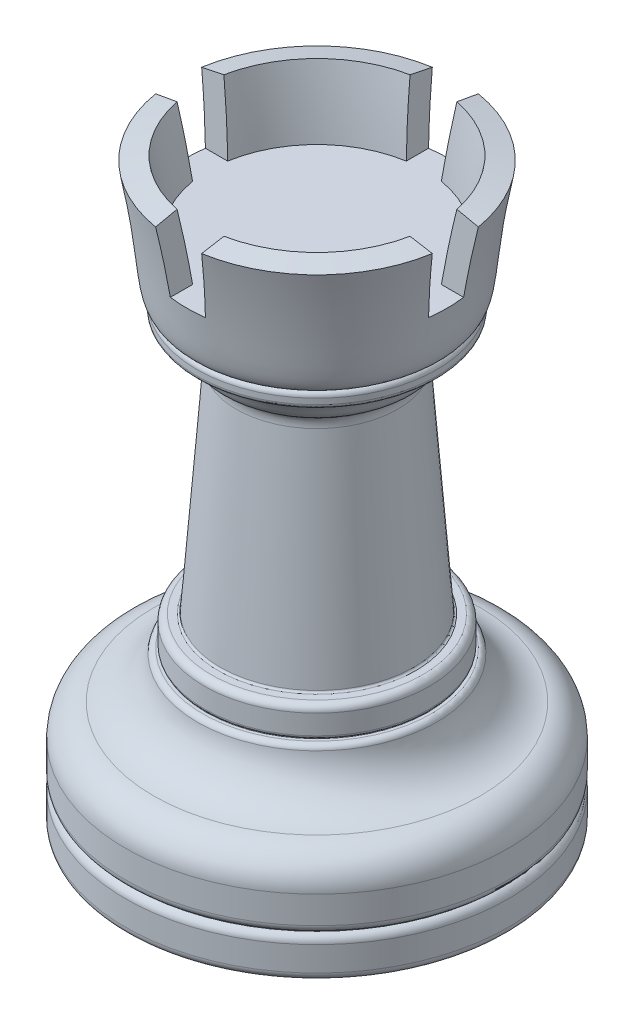
SolidWorks part; units mm, degrees
ref_plane "Front Plane" through (0, 0, 0) normal (0, 0, 1) x (1, 0, 0)
ref_plane "Top Plane" through (0, 0, 0) normal (0, 1, 0) x (1, 0, 0)
ref_plane "Right Plane" through (0, 0, 0) normal (1, 0, 0) x (0, 0, -1)
sketch "Sketch1" plane through (0, 0, 0) normal (0, 0, 1) x (1, 0, 0)
  line L0 (0, 0) -> (0, 95.25) construction
  dimension "D1" = 95.25
sketch "Sketch2" plane through (0, 0, 0) normal (0, 0, 1) x (1, 0, 0)
  line L0 (0, 0) -> (191.1891, 0) construction
  line L1 (185.0871, 5.2387) -> (185.0871, 53.028)
  line L2 (174.4785, 19.6016) -> (174.6126, 19.6016)
  line L3 (185.0871, 5.2387) -> (168.0691, 5.2387)
  line L4 (167.3071, 6.0007) -> (167.3071, 8.2867)
  line L5 (167.3071, 9.8107) -> (167.3071, 12.3507)
  line L6 (174.6277, 19.9236) -> (174.6277, 21.7489)
  line L7 (175.2498, 22.3709) -> (175.9016, 22.3709)
  line L8 (170.8832, 9.0487) -> (185.0871, 9.0487) construction
  line L9 (167.8151, 9.0923) -> (167.8151, 9.0051)
  line L10 (185.0871, 5.2387) -> (185.0871, 0) construction
  line L11 (176.09, 22.5456) -> (177.5963, 42.5634)
  line L12 (173.9246, 47.6069) -> (173.9246, 47.0859)
  line L13 (173.9246, 46.8206) -> (173.9246, 47.3511) construction
  line L14 (174.7569, 19.6016) -> (174.6126, 19.6016)
  line L15 (174.2739, 48.1387) -> (174.2739, 48.1076)
  line L18 (173.8677, 48.5724) -> (173.8677, 53.028)
  line L19 (173.8677, 53.028) -> (185.0871, 53.028)
  arc A0 (169.9128, 15.2736) -> (173.9767, 19.1725) centre (169.3806, 19.8957) ccw
  arc A1 (173.8677, 48.5724) -> (174.2739, 48.1387) centre (174.3437, 48.6112) ccw
  arc A2 (174.2739, 48.1076) -> (173.9246, 47.6069) centre (174.458, 47.6069) ccw
  arc A3 (173.9767, 19.1725) -> (174.4785, 19.6016) centre (174.4785, 19.0936) cw
  arc A4 (169.9128, 15.2736) -> (167.3071, 12.3507) centre (170.2493, 12.3507) ccw
  arc A5 (167.3071, 9.8107) -> (167.8151, 9.0923) centre (168.0691, 9.8107) ccw
  arc A6 (167.8151, 9.0051) -> (167.3071, 8.2867) centre (168.0691, 8.2867) ccw
  arc A7 (168.0691, 5.2387) -> (167.3071, 6.0007) centre (168.0691, 6.0007) cw
  arc A8 (175.2498, 22.3709) -> (174.6277, 21.7489) centre (175.2498, 21.7489) ccw
  arc A9 (174.6277, 19.9236) -> (174.7764, 19.6486) centre (174.9565, 19.9236) ccw
  arc A10 (174.7764, 19.6486) -> (174.7569, 19.6016) centre (174.7569, 19.6291) cw
  arc A11 (175.9016, 22.3709) -> (176.09, 22.5456) centre (175.9016, 22.5598) ccw
  spline S0 degree 3 poles (173.9246, 47.0859) (173.9246, 46.4935) (175.4388, 46.4365) (176.1024, 44.4908) (176.6911, 44.0421) (177.3021, 43.703) (177.6576, 43.3781) (177.5963, 42.5634) knots 0 0 0 0 0.353428 0.425175 0.684993 0.745723 1 1 1 1
  dimension "D2" = 5.2387
  dimension "D3" = 0.508
  dimension "D4" = 0.1889
  dimension "D5" = 0.762
  dimension "D6" = 0.762
  dimension "D13" = 17.78
  dimension "D11" = 3.81
  dimension "D12" = 3.302
  dimension "D14" = 0.508
  dimension "D15" = 191.1891
revolve "Revolve2" add sketch "Sketch2" angle 360 about L1
sketch "Sketch4" plane through (0, 0, 0) normal (0, 0, 1) x (1, 0, 0)
  line L0 (173.4091, 48.1342) -> (175.2783, 48.1342) construction
  line L1 (172.0471, 58.8686) -> (174.0406, 59.2622)
  line L2 (175.404, 49.823) -> (174.2739, 48.1342)
  line L3 (185.0871, 53.028) -> (185.0871, 51.0793) construction
  line L4 (196.3064, 53.028) -> (173.8677, 53.028) construction
  line L5 (185.0871, 59.2622) -> (185.0871, 50.1856) construction
  line L6 (174.2739, 48.1387) -> (174.2739, 48.1076) construction
  spline S0 degree 3 poles (174.2739, 48.1342) (172.9685, 48.1342) (173.6032, 50.9866) (172.0471, 58.8686) knots 0 0 0 0 1 1 1 1
  spline S1 degree 1 poles (175.404, 49.823) (174.0406, 59.2622) knots 0 0 1 1 construction
  spline S2 degree 3 poles (175.404, 49.823) (175.3894, 49.907) (175.3647, 50.0631) (175.308, 50.4749) (175.2355, 51.0976) (175.1347, 52.0252) (175.0109, 53.1219) (174.8523, 54.3889) (174.6479, 55.8262) (174.4288, 57.1731) (174.2205, 58.3321) (174.101, 58.9562) (174.0406, 59.2622) knots 0.378082 0.378082 0.378082 0.378082 0.416952 0.455822 0.533561 0.611301 0.689041 0.766781 0.84452 0.92226 0.96113 1 1 1 1
  dimension "D1" = 2.032
revolve "Revolve3" add sketch "Sketch4" angle 360 about L5
ref_plane "Plane1" through (0, 59.2622, 0) normal (0, -1, 0) x (-1, 0, 0)
sketch "Sketch5" plane through (0, 59.2622, 0) normal (0, -1, 0) x (-1, 0, 0)
  line L0 (-187.2626, 2.1755) -> (-187.2626, 19.9971)
  line L1 (-182.9116, -19.9971) -> (-187.2626, -19.9971)
  line L2 (-182.9116, -19.9971) -> (-182.9116, -2.1755)
  line L3 (-182.9116, 19.9971) -> (-187.2626, 19.9971)
  line L4 (-187.2626, -19.9971) -> (-187.2626, -2.1755)
  line L5 (-182.9116, -19.9971) -> (-187.2626, 19.9971) construction
  line L6 (-182.9116, 19.9971) -> (-187.2626, -19.9971) construction
  line L7 (-165.0899, -2.1755) -> (-182.9116, -2.1755)
  line L8 (-165.0899, -2.1755) -> (-165.0899, 2.1755)
  line L9 (-165.0899, 2.1755) -> (-182.9116, 2.1755)
  line L10 (-205.0842, -2.1755) -> (-205.0842, 2.1755)
  line L11 (-165.0899, -2.1755) -> (-205.0842, 2.1755) construction
  line L12 (-165.0899, 2.1755) -> (-205.0842, -2.1755) construction
  line L13 (-187.2626, 2.1755) -> (-205.0842, 2.1755)
  line L14 (-187.2626, -2.1755) -> (-205.0842, -2.1755)
  line L15 (-182.9116, 2.1755) -> (-182.9116, 19.9971)
  point P0 (-185.0871, 0)
  point P6 (-185.0871, 0)
extrude "Cut-Extrude2" cut sketch "Sketch5" along normal up to surface (6.2342 mm away) draft 5
